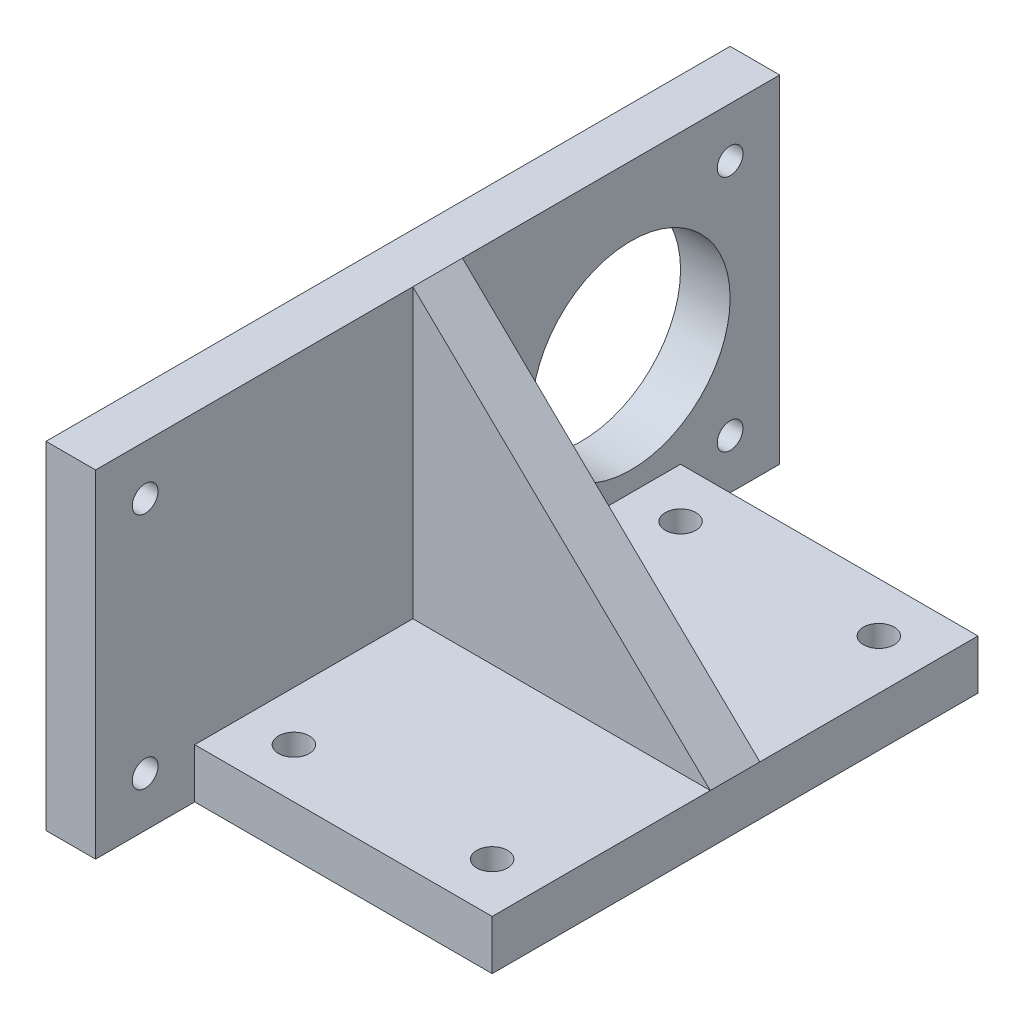
SolidWorks part; units mm, degrees
ref_plane "Front Plane" through (0, 0, 0) normal (0, 0, 1) x (1, 0, 0)
ref_plane "Top Plane" through (0, 0, 0) normal (0, 1, 0) x (1, 0, 0)
ref_plane "Right Plane" through (0, 0, 0) normal (1, 0, 0) x (0, 0, -1)
sketch "Sketch1" plane through (0, 0, 0) normal (1, 0, 0) x (0, 0, -1)
  line L0 (55, 0) -> (-55, 0) construction
  line L5 (-29.5, 12) -> (29.5, -12) construction
  line L6 (-29.5, -12) -> (29.5, 12) construction
  line L7 (-34.5, 17) -> (34.5, 17)
  line L8 (-34.5, 17) -> (-34.5, -17)
  line L9 (-34.5, -17) -> (34.5, -17)
  line L10 (34.5, 17) -> (34.5, -17)
  circle A0 centre (-29.5, 12) radius 1.3
  circle A1 centre (-29.5, -12) radius 1.3
  circle A2 centre (29.5, 12) radius 1.3
  circle A3 centre (29.5, -12) radius 1.3
  circle A4 centre (19.5, 0) radius 10
  point P0 (0, 0)
  dimension "D1" = 2.6
  dimension "D3" = 59
  dimension "D9" = 20
  dimension "D2" = 24
  dimension "D4" = 5
  dimension "D5" = 5
  dimension "D6" = 5
  dimension "D7" = 5
  dimension "D8" = 10
extrude "Boss-Extrude1" add sketch "Sketch1" along normal blind 5
sketch "Sketch2" plane through (5, 0, 0) normal (1, 0, 0) x (0, 0, -1)
  line L0 (-34.5, -17) -> (34.5, -17) construction
  line L1 (-24.5, -17) -> (24.5, -17)
  line L2 (-24.5, -17) -> (-24.5, -12)
  line L3 (-24.5, -12) -> (24.5, -12)
  line L4 (24.5, -17) -> (24.5, -12)
  line L5 (-34.5, 17) -> (-34.5, -17) construction
  line L6 (34.5, -17) -> (34.5, 17) construction
  dimension "D1" = 10
  dimension "D2" = 10
  dimension "D3" = 5
extrude "Boss-Extrude2" add sketch "Sketch2" along normal blind 30
sketch "Sketch3" plane through (0, 0, 0) normal (0, 0, 1) x (1, 0, 0)
  line L0 (5, -12) -> (35, -12)
  line L1 (35, -12) -> (5, 17)
  line L2 (5, 17) -> (5, -12)
extrude "Boss-Extrude3" add sketch "Sketch3" along normal mid plane 5
sketch "Sketch4" plane through (0, -17, 0) normal (0, -1, 0) x (1, 0, 0)
  line L0 (35, 24.5) -> (35, -24.5) construction
  line L1 (35, 24.5) -> (5, 24.5) construction
  line L2 (55, 0) -> (-55, 0) construction
  circle A0 centre (30, 19.5) radius 1.55
  circle A2 centre (10, 19.5) radius 1.55
  circle A3 centre (10, -19.5) radius 1.55
  circle A4 centre (30, -19.5) radius 1.55
  dimension "D1" = 3.1
  dimension "D2" = 5
  dimension "D3" = 5
  dimension "D4" = 20
extrude "Cut-Extrude1" cut sketch "Sketch4" against normal blind 5
